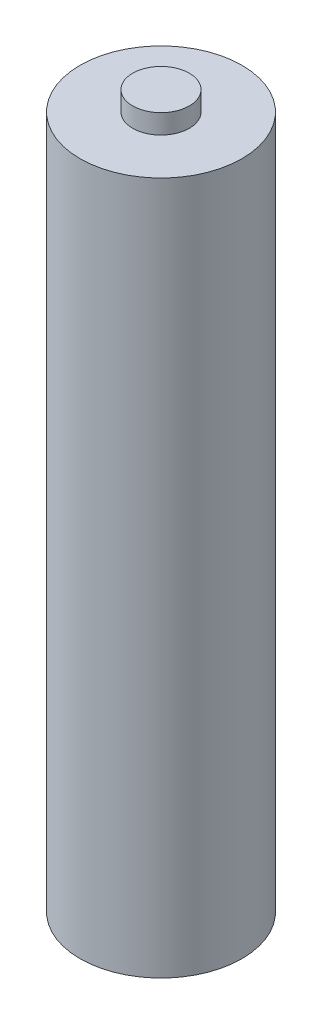
SolidWorks part; units mm, degrees
ref_plane "前视基准面" through (0, 0, 0) normal (0, 0, 1) x (1, 0, 0)
ref_plane "上视基准面" through (0, 0, 0) normal (0, 1, 0) x (1, 0, 0)
ref_plane "右视基准面" through (0, 0, 0) normal (1, 0, 0) x (0, 0, -1)
other "Configuration Table"
sketch "草图1" plane through (0, 0, 0) normal (1, 0, 0) x (0, 0, -1)
  line L1 (0, 0) -> (5, 0)
  line L2 (0, 0) -> (0, -42.8)
  line L3 (0, -42.8) -> (5, -42.8)
  line L4 (5, 0) -> (5, -42.8)
  line L5 (0, 0) -> (1.75, 0)
  line L6 (0, 0) -> (0, 1.2)
  line L7 (0, 1.2) -> (1.75, 1.2)
  line L8 (1.75, 0) -> (1.75, 1.2)
  dimension "D1" = 1.75
  dimension "D2" = 1.2
  dimension "D3" = 44
  dimension "D4" = 5
revolve "旋转1" add sketch "草图1" angle 360 about L2
